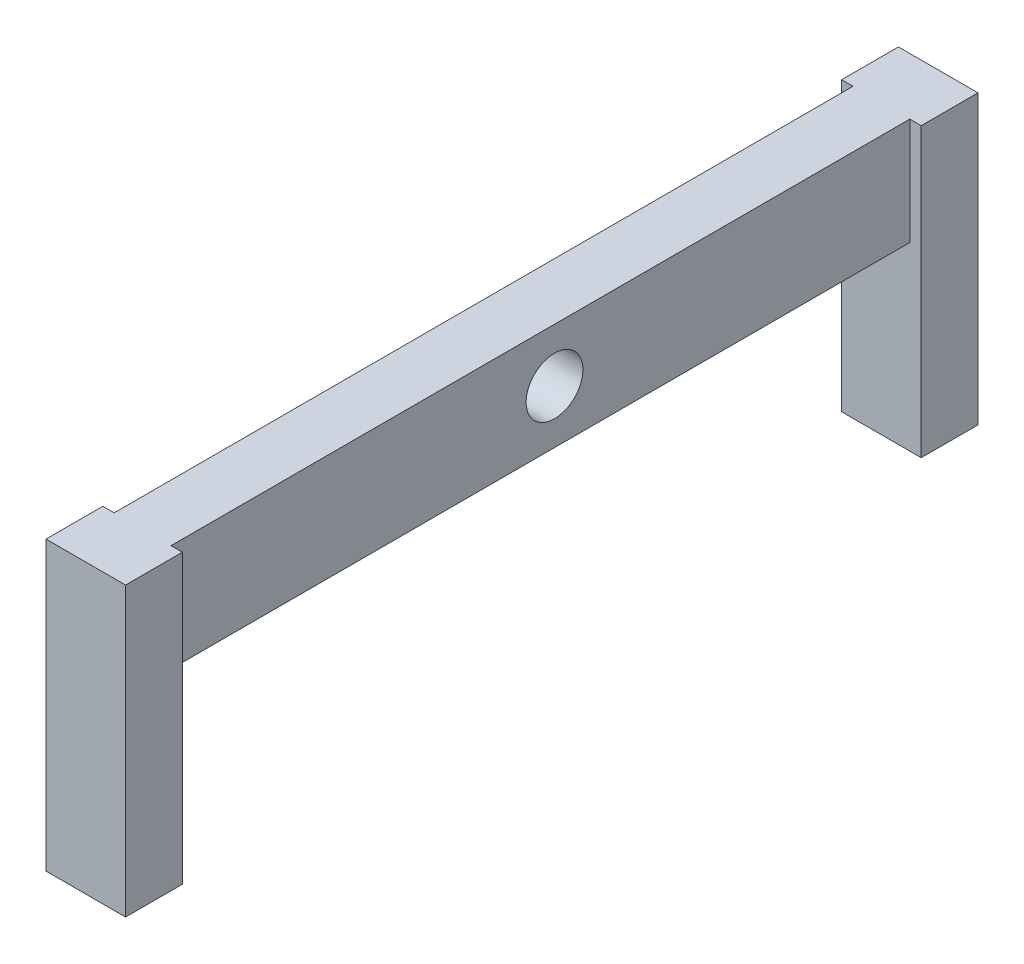
SolidWorks part; units mm, degrees
material "201.0-T6 Insulated Mold Casting (SS)"
ref_plane "Front Plane" through (0, 0, 0) normal (0, 0, 1) x (1, 0, 0)
ref_plane "Top Plane" through (0, 0, 0) normal (0, 1, 0) x (1, 0, 0)
ref_plane "Right Plane" through (0, 0, 0) normal (1, 0, 0) x (0, 0, -1)
sketch "Sketch1" plane through (0, 0, 0) normal (0, 1, 0) x (1, 0, 0)
  line L1 (-474.1379, 241.1638) -> (-424.1379, 241.1638)
  line L2 (-474.1379, 241.1638) -> (-474.1379, -508.8362)
  line L3 (-474.1379, -508.8362) -> (-424.1379, -508.8362)
  line L4 (-424.1379, 241.1638) -> (-424.1379, -508.8362)
  dimension "D1" = 750
  dimension "D2" = 50
extrude "Boss-Extrude1" add sketch "Sketch1" along normal blind 94
sketch "Sketch2" plane through (0, 94, 0) normal (0, 1, 0) x (1, 0, 0)
  line L0 (-474.1379, 241.1638) -> (-484.1379, 241.1638)
  line L4 (-484.1379, 191.1638) -> (-484.1379, 241.1638)
  line L6 (-424.1379, 241.1638) -> (-414.1379, 241.1638)
  line L7 (-414.1379, 241.1638) -> (-414.1379, 191.1638)
  line L8 (-414.1379, 191.1638) -> (-484.1379, 191.1638)
  line L9 (-474.1379, 241.1638) -> (-424.1379, 241.1638)
  line L10 (-424.1379, -133.8362) -> (-474.1379, -133.8362)
  line L11 (-424.1379, -508.8362) -> (-424.1379, 241.1638) construction
  line L12 (-474.1379, 241.1638) -> (-474.1379, -508.8362) construction
  line L13 (-474.1379, -508.8362) -> (-424.1379, -508.8362)
  line L14 (-414.1379, -458.8362) -> (-484.1379, -458.8362)
  line L15 (-414.1379, -508.8362) -> (-414.1379, -458.8362)
  line L16 (-424.1379, -508.8362) -> (-414.1379, -508.8362)
  line L17 (-484.1379, -458.8362) -> (-484.1379, -508.8362)
  line L18 (-474.1379, -508.8362) -> (-484.1379, -508.8362)
  line M6 (-474.1379, 241.1638) -> (-474.1379, -508.8362)
  line M7 (-474.1379, -508.8362) -> (-424.1379, -508.8362)
  line M8 (-424.1379, -508.8362) -> (-424.1379, 241.1638)
  line M9 (-424.1379, 241.1638) -> (-474.1379, 241.1638)
  dimension "D2" = 10
  dimension "D3" = 50
extrude "Boss-Extrude2" add sketch "Sketch2" against normal blind 253 contours L8 L0 L4 M6 | L8 M8 M9 M6 | L8 L7 L6 M8 | L18 L14 L17 M6 | L16 L15 L14 M8 | L14 M8 M6 M7
sketch "Sketch3" plane through (-474.1379, 0, 0) normal (-1, 0, 0) x (0, 0, 1)
  line L1 (-191.1638, -159) -> (-191.1638, 94) construction
  circle A0 centre (-137.6638, 47) radius 20
  circle A1 centre (405.3362, 47) radius 20
  dimension "D1" = 543
  dimension "D2" = 53.5
extrude "Cut-Extrude1" cut sketch "Sketch3" against normal blind 10
sketch "Sketch4" plane through (-424.1379, 0, 0) normal (1, 0, 0) x (0, 0, -1)
  line L0 (-458.8362, -159) -> (-458.8362, 94) construction
  circle A0 centre (-121.4362, 47) radius 25
  dimension "D1" = 337.4
extrude "Cut-Extrude2" cut sketch "Sketch4" against normal through all both and the other way through all
